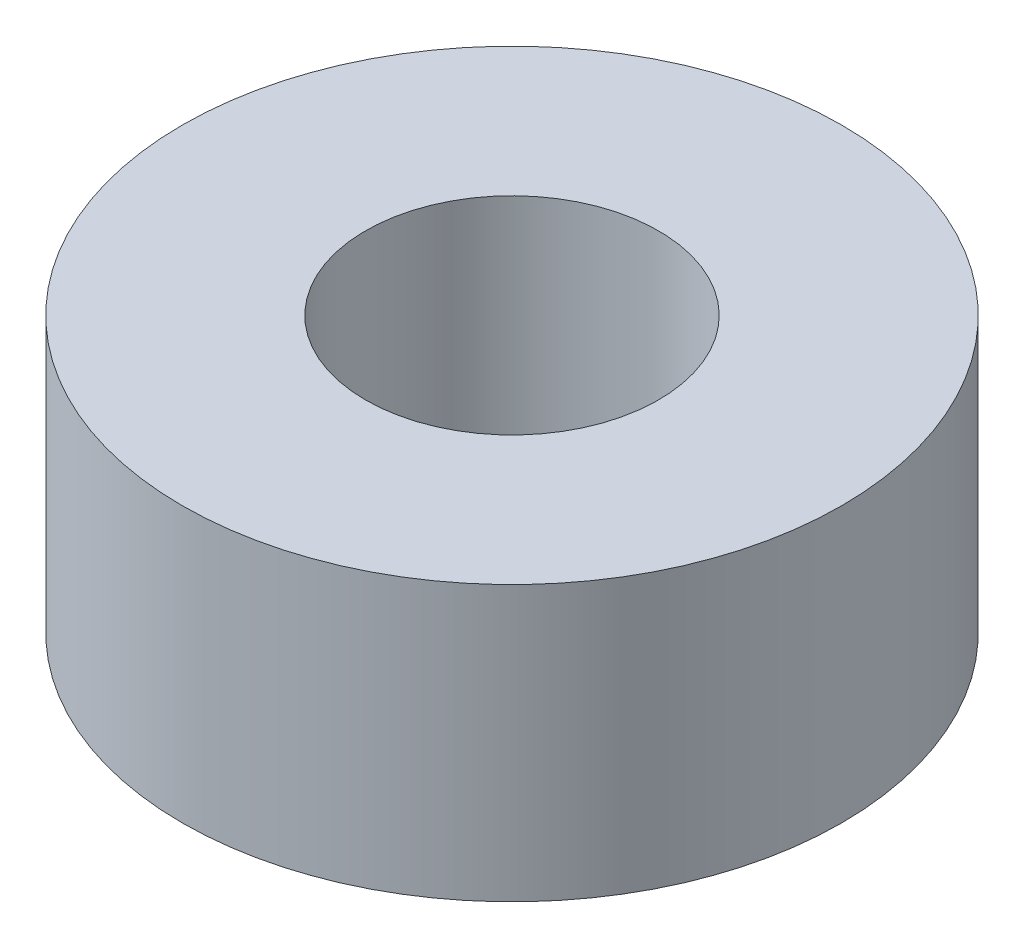
SolidWorks part; units mm, degrees
ref_plane "Plano frontal" through (0, 0, 0) normal (0, 0, 1) x (1, 0, 0)
ref_plane "Plano superior" through (0, 0, 0) normal (0, 1, 0) x (1, 0, 0)
ref_plane "Plano direito" through (0, 0, 0) normal (1, 0, 0) x (0, 0, -1)
sketch "Esboço1" plane through (0, 0, 0) normal (0, 1, 0) x (1, 0, 0)
  circle A0 centre (0, 0) radius 1.6
  circle A1 centre (0, 0) radius 3.6
  dimension "D1" = 3.2
  dimension "D2" = 2
extrude "Ressalto-extrusão1" add sketch "Esboço1" along normal blind 3
